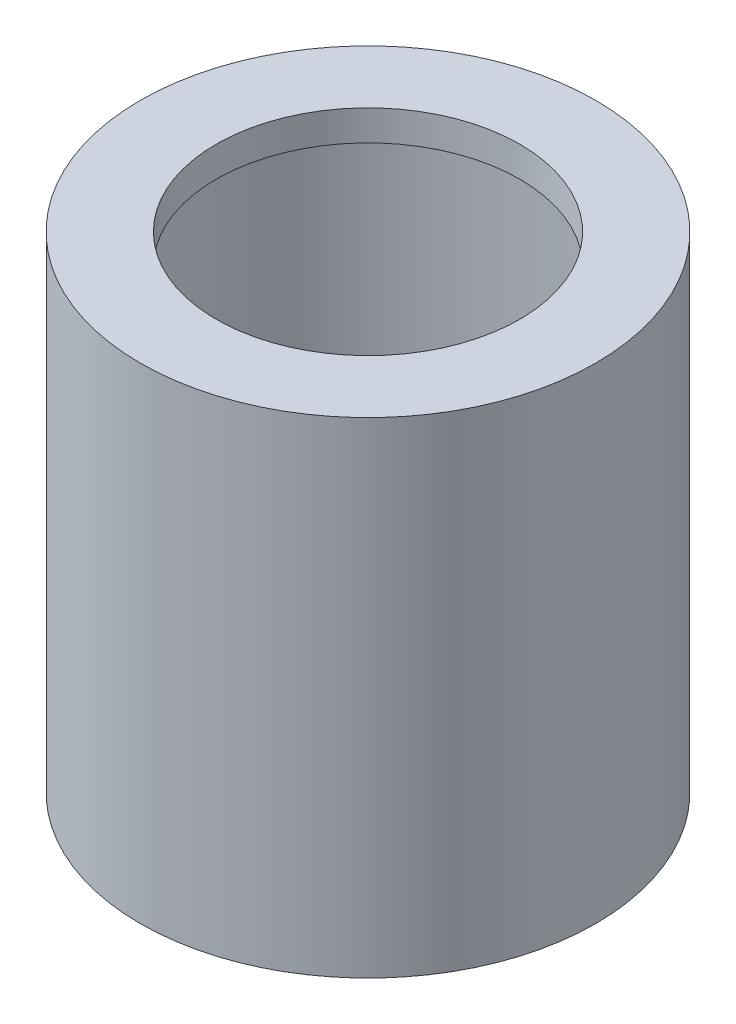
SolidWorks part; units mm, degrees
ref_plane "Front Plane" through (0, 0, 0) normal (0, 0, 1) x (1, 0, 0)
ref_plane "Top Plane" through (0, 0, 0) normal (0, 1, 0) x (1, 0, 0)
ref_plane "Right Plane" through (0, 0, 0) normal (1, 0, 0) x (0, 0, -1)
sketch "Sketch1" plane through (0, 0, 0) normal (0, 0, 1) x (1, 0, 0)
  line L0 (0, 0) -> (0, 25.3876) construction
  line L2 (-11.9062, 25.3876) -> (-11.9062, 0)
  line L3 (-11.9062, 0) -> (-11.1125, 0)
  line L4 (-11.1125, 23.8001) -> (-11.1125, 0)
  line L5 (-11.9062, 25.3876) -> (0, 25.3876) construction
  line L6 (-11.1125, 0) -> (0, 0) construction
  line L7 (-11.9062, 25.3876) -> (-7.9375, 25.3876)
  line L8 (-7.9375, 25.3876) -> (-7.9375, 23.8001)
  line L9 (-7.9375, 23.8001) -> (-11.1125, 23.8001)
  dimension "D1" = 0.7937
  dimension "D2" = 25.4
  dimension "D3" = 11.1125
  dimension "D4" = 7.9375
  dimension "D5" = 1.5875
revolve "Revolve1" add sketch "Sketch1" angle 360 about L0
